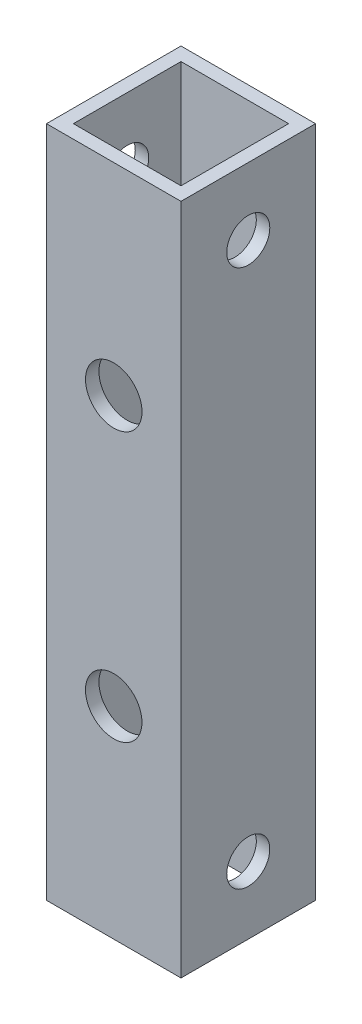
SolidWorks part; units mm, degrees
material "1060 合金"
ref_plane "正面" through (0, 0, 0) normal (0, 0, 1) x (1, 0, 0)
ref_plane "平面" through (0, 0, 0) normal (0, 1, 0) x (1, 0, 0)
ref_plane "右側面" through (0, 0, 0) normal (1, 0, 0) x (0, 0, -1)
sketch "ｽｹｯﾁ1" plane through (0, 0, 0) normal (0, 1, 0) x (1, 0, 0)
  line L1 (-5, 5) -> (5, 5)
  line L2 (-5, 5) -> (-5, -5)
  line L3 (-5, -5) -> (5, -5)
  line L4 (5, 5) -> (5, -5)
  line L5 (-5, 5) -> (5, -5) construction
  line L6 (-5, -5) -> (5, 5) construction
  point P0 (0, 0)
  dimension "D1" = 10
extrude "押し出し-薄板1" add sketch "ｽｹｯﾁ1" along normal blind 50 thin
sketch "ｽｹｯﾁ2" plane through (5, 0, 0) normal (1, 0, 0) x (0, 0, -1)
  line L0 (-5, 25) -> (5, 25) construction
  line L1 (-5, 50) -> (-5, 0) construction
  line L2 (5, 50) -> (5, 0) construction
  line L3 (0, 25) -> (0, 45) construction
  circle A0 centre (0, 45) radius 1.6
  circle A1 centre (0, 5) radius 1.6
  dimension "D1" = 3.2
  dimension "D2" = 40
extrude "ｶｯﾄ - 押し出し1" cut sketch "ｽｹｯﾁ2" against normal through all
sketch "ｽｹｯﾁ3" plane through (0, 0, 5) normal (0, 0, 1) x (1, 0, 0)
  line L0 (-5, 25) -> (5, 25) construction
  line L1 (-5, 50) -> (-5, 0) construction
  line L2 (5, 50) -> (5, 0) construction
  line L3 (0, 25) -> (0, 35) construction
  circle A0 centre (0, 35) radius 2.1
  circle A1 centre (0, 15) radius 2.1
  dimension "D1" = 4.2
  dimension "D2" = 20
extrude "ｶｯﾄ - 押し出し2" cut sketch "ｽｹｯﾁ3" against normal through all
